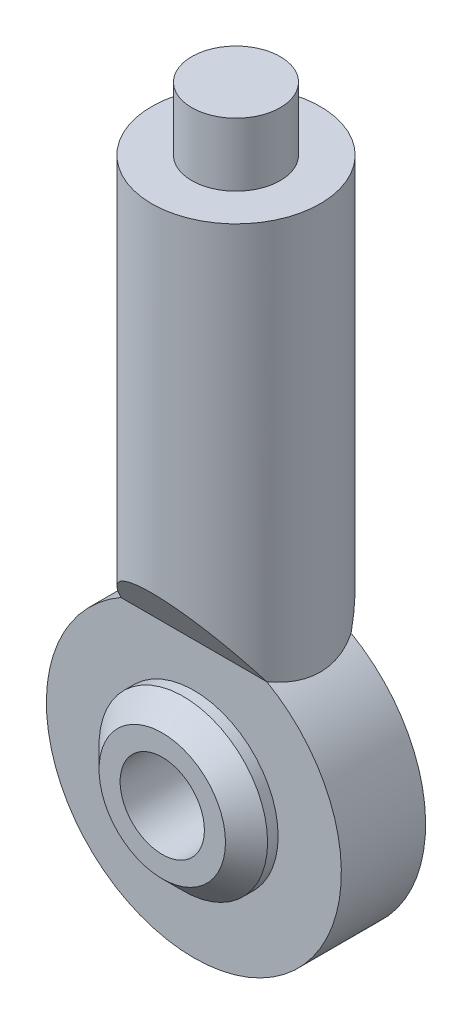
SolidWorks part; units mm, degrees
ref_plane "前视基准面" through (0, 0, 0) normal (0, 0, 1) x (1, 0, 0)
ref_plane "上视基准面" through (0, 0, 0) normal (0, 1, 0) x (1, 0, 0)
ref_plane "右视基准面" through (0, 0, 0) normal (1, 0, 0) x (0, 0, -1)
sketch "草图1" plane through (0, 0, 0) normal (0, 0, 1) x (1, 0, 0)
  circle A0 centre (0, 0) radius 4
  circle A1 centre (0, 0) radius 7
extrude "凸台-拉伸1" add sketch "草图1" along normal mid plane 4
sketch "草图2" plane through (0, 0, 0) normal (0, 0, 1) x (1, 0, 0)
  circle A0 centre (0, 0) radius 4
  circle A1 centre (0, 0) radius 2
extrude "凸台-拉伸2" add sketch "草图2" along normal mid plane 7
chamfer "倒角1" distance 1 angle 45 2 edges at (4, 0, -3.5) (4, 0, 3.5)
sketch "草图3" plane through (0, 0, 0) normal (1, 0, 0) x (0, 0, -1)
  line L0 (0, 0) -> (0, 25)
ref_plane "基准面1" through (0, 25, 0) normal (0, 1, 0) x (1, 0, 0)
sketch "草图4" plane through (0, 25, 0) normal (0, 1, 0) x (1, 0, 0)
  circle A0 centre (0, 0) radius 4
extrude "凸台-拉伸3" add sketch "草图4" against normal blind 20
sketch "草图6" plane through (0, 5, 0) normal (0, -1, 0) x (1, 0, 0)
  line L0 (-3.4641, 2) -> (3.4641, 2)
  line L1 (3.4641, 2) -> (1.3795, 5.7796)
  line L2 (1.3795, 5.7796) -> (-7.3551, 6.8798)
  line L3 (-7.3551, 6.8798) -> (-3.4641, 2)
sketch "草图7" plane through (0, 0, 0) normal (1, 0, 0) x (0, 0, -1)
  line L0 (2, 5) -> (4, 9)
  line L1 (4, 5) -> (4, 25) construction
  line L2 (4, 9) -> (4, 5)
  line L3 (4, 5) -> (2, 5)
  line L4 (-2, 5) -> (-4, 9)
  line L5 (-4, 9) -> (-4, 5)
  line L6 (-6.8798, 5) -> (-2, 5) construction
  line L7 (-4, 5) -> (-2, 5)
extrude "切除-拉伸1" cut sketch "草图7" against normal mid plane 10
sketch "草图8" plane through (0, 0, 0) normal (1, 0, 0) x (0, 0, -1)
  line L0 (-2, 5) -> (-2, 6.0828)
  line L1 (-2, 6.0828) -> (-4, 9)
  line L2 (-4, 9) -> (-2, 5)
  line L3 (2, 5) -> (2, 6.0828)
  line L4 (2, 6.0828) -> (4, 9)
  line L5 (4, 9) -> (2, 5)
extrude "切除-拉伸2" cut sketch "草图8" against normal mid plane 10
sketch "草图9" plane through (0, 25, 0) normal (0, 1, 0) x (1, 0, 0)
  circle A0 centre (0, 0) radius 2.1
extrude "凸台-拉伸4" add sketch "草图9" along normal blind 3
